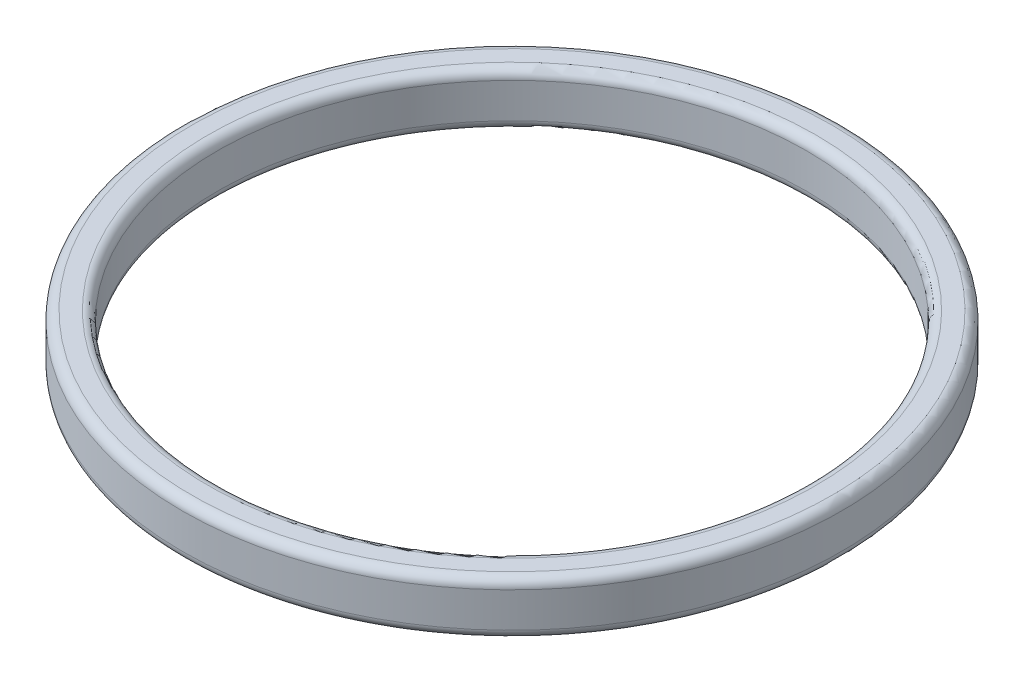
SolidWorks part; units mm, degrees
material "Резина"
ref_plane "Спереди" through (0, 0, 0) normal (0, 0, 1) x (1, 0, 0)
ref_plane "Сверху" through (0, 0, 0) normal (0, 1, 0) x (1, 0, 0)
ref_plane "Справа" through (0, 0, 0) normal (1, 0, 0) x (0, 0, -1)
sketch "Эскиз1" plane through (0, 0, 0) normal (0, 0, 1) x (1, 0, 0)
  line L0 (0, 0) -> (0, 8.6241) construction
  line L1 (-16.5, 0) -> (-17.4, 0)
  line L2 (-16, 0.5) -> (-16, 2.4)
  line L3 (-16.5, 2.9) -> (-17.4, 2.9)
  line L4 (-17.9, 0.5) -> (-17.9, 2.4)
  arc A0 (-17.4, 0) -> (-17.9, 0.5) centre (-17.4, 0.5) cw
  arc A1 (-16, 0.5) -> (-16.5, 0) centre (-16.5, 0.5) cw
  arc A2 (-16, 2.4) -> (-16.5, 2.9) centre (-16.5, 2.4) ccw
  arc A3 (-17.9, 2.4) -> (-17.4, 2.9) centre (-17.4, 2.4) cw
  point P9 (-17.9, 0)
  point P12 (-16, 0)
  point P15 (-16, 2.9)
  dimension "D4" = 0.5
  dimension "D1" = 17.9
  dimension "D2" = 1.9
  dimension "D3" = 2.9
revolve "Повернуть1" add sketch "Эскиз1" angle 360 about L0
